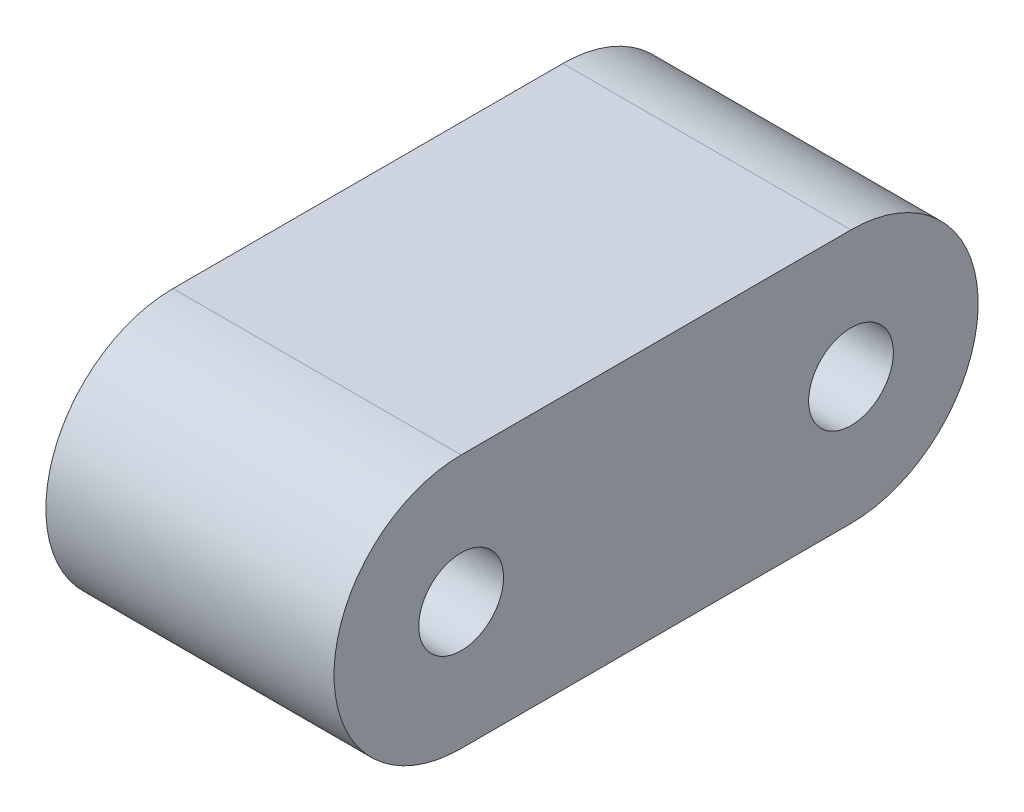
SolidWorks part; units mm, degrees
ref_plane "Alzado" through (0, 0, 0) normal (0, 0, 1) x (1, 0, 0)
ref_plane "Planta" through (0, 0, 0) normal (0, 1, 0) x (1, 0, 0)
ref_plane "Vista lateral" through (0, 0, 0) normal (1, 0, 0) x (0, 0, -1)
sketch "Croquis1" plane through (0, 0, 0) normal (1, 0, 0) x (0, 0, -1)
  line L0 (-11.5, 0) -> (11.5, 0) construction
  line L1 (-11.5, 7.5) -> (11.5, 7.5)
  line L2 (-11.5, -7.5) -> (11.5, -7.5)
  circle A0 centre (-11.5, 0) radius 2.5
  circle A1 centre (11.5, 0) radius 2.5
  arc A2 (-11.5, 7.5) -> (-11.5, -7.5) centre (-11.5, 0) ccw
  arc A3 (11.5, -7.5) -> (11.5, 7.5) centre (11.5, 0) ccw
  point P3 (0, 0)
  dimension "D1" = 5
  dimension "D3" = 15
  dimension "D2" = 23
extrude "Saliente-Extruir1" add sketch "Croquis1" along normal mid plane 17
